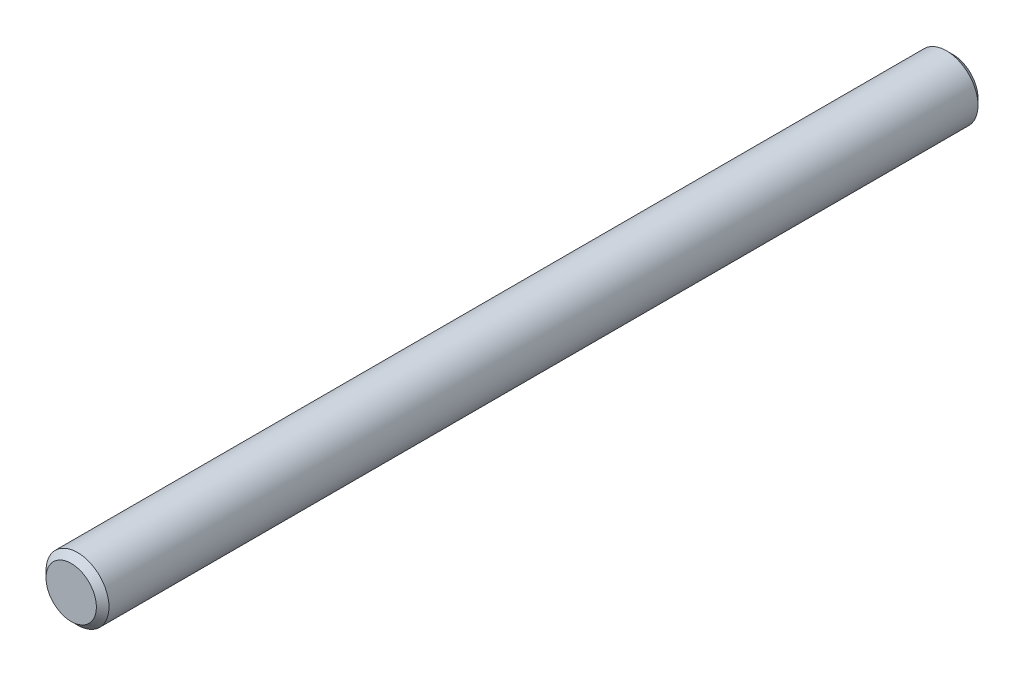
SolidWorks part; units mm, degrees
ref_plane "Face" through (0, 0, 0) normal (0, 0, 1) x (1, 0, 0)
ref_plane "Dessus" through (0, 0, 0) normal (0, 1, 0) x (1, 0, 0)
ref_plane "Droite" through (0, 0, 0) normal (1, 0, 0) x (0, 0, -1)
sketch "Esquisse1" plane through (0, 0, 0) normal (0, 0, 1) x (1, 0, 0)
  circle A0 centre (0, 0) radius 1
extrude "Extrusion1" add sketch "Esquisse1" along normal blind 28
chamfer "Chanfrein1" distance 0.2 angle 45 2 edges at (1, 0, 0) (1, 0, 28)
